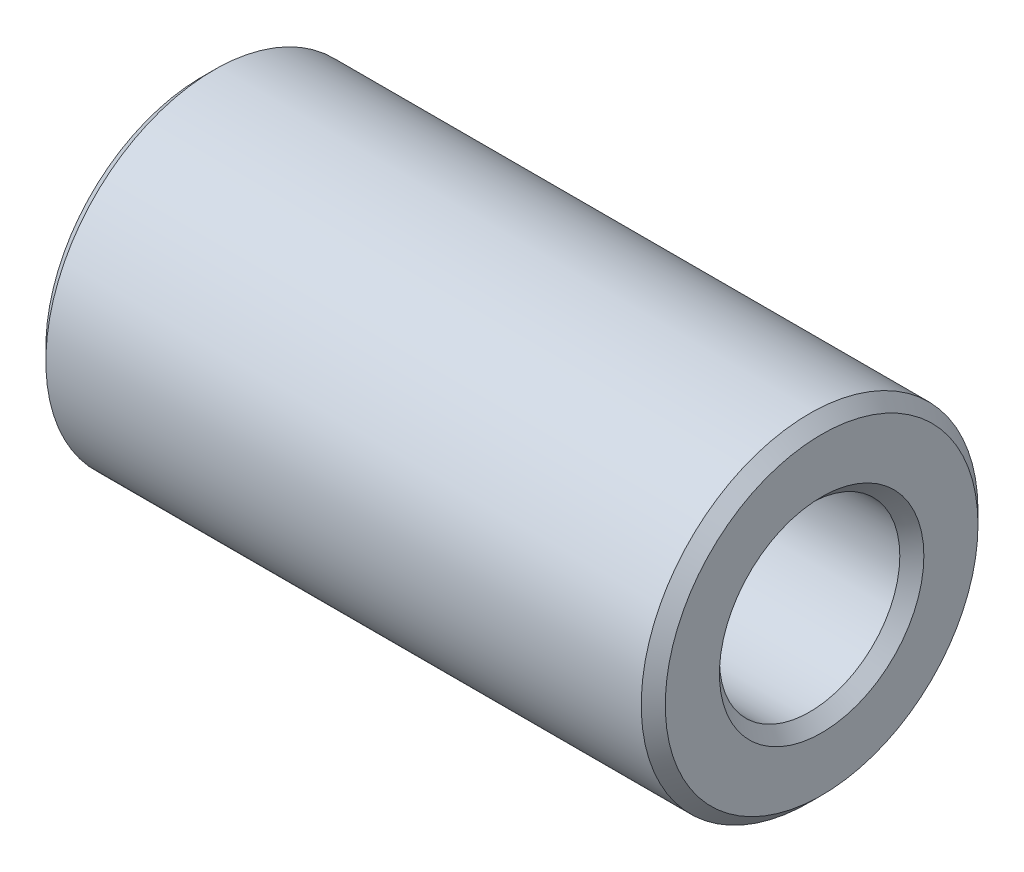
SolidWorks part; units mm, degrees
material "S355JR"
ref_plane "Front" through (0, 0, 0) normal (0, 0, 1) x (1, 0, 0)
ref_plane "Top" through (0, 0, 0) normal (0, 1, 0) x (1, 0, 0)
ref_plane "Right" through (0, 0, 0) normal (1, 0, 0) x (0, 0, -1)
sketch "Sketch1" plane through (0, 0, 0) normal (1, 0, 0) x (0, -1, 0)
  circle A0 centre (0, 0) radius 14
  circle A1 centre (0, 0) radius 7.5
  dimension "D1" = 28
  dimension "D2" = 15
extrude "Boss-Extrude1" add sketch "Sketch1" along normal mid plane 51.5
chamfer "Chamfer1" distance 1 angle 45 4 edges at (-25.75, 0, -7.5) (-25.75, 0, -14) (25.75, 0, -7.5) (25.75, 0, -14)
